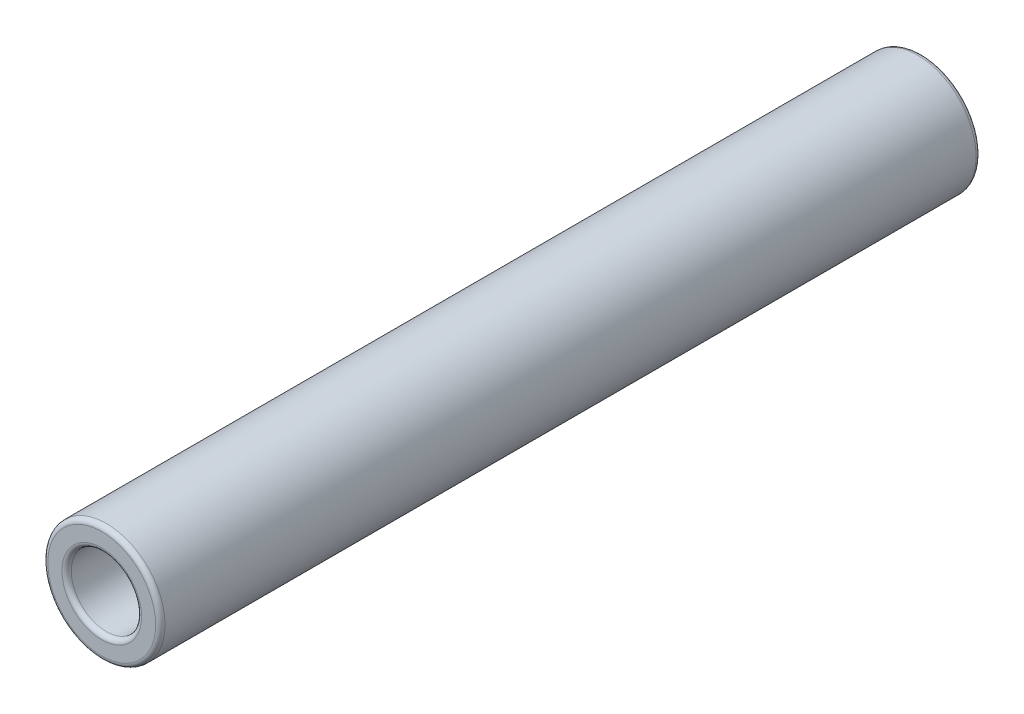
SolidWorks part; units mm, degrees
ref_plane "Alzado" through (0, 0, 0) normal (0, 0, 1) x (1, 0, 0)
ref_plane "Planta" through (0, 0, 0) normal (0, 1, 0) x (1, 0, 0)
ref_plane "Vista lateral" through (0, 0, 0) normal (1, 0, 0) x (0, 0, -1)
sketch "Croquis1" plane through (0, 0, 0) normal (0, 1, 0) x (1, 0, 0)
  line L0 (1.5, 17.3) -> (1.5, -17.3)
  line L1 (1.7, -17.5) -> (2.3, -17.5)
  line L2 (2.5, -17.3) -> (2.5, 17.3)
  line L3 (2.3, 17.5) -> (1.7, 17.5)
  line L4 (0, 17.5025) -> (0, -17.5025) construction
  arc A0 (1.7, 17.5) -> (1.5, 17.3) centre (1.7, 17.3) ccw
  arc A1 (1.5, -17.3) -> (1.7, -17.5) centre (1.7, -17.3) ccw
  arc A2 (2.3, -17.5) -> (2.5, -17.3) centre (2.3, -17.3) ccw
  arc A3 (2.5, 17.3) -> (2.3, 17.5) centre (2.3, 17.3) ccw
revolve "Revolución1" add sketch "Croquis1" angle 360 about L4
